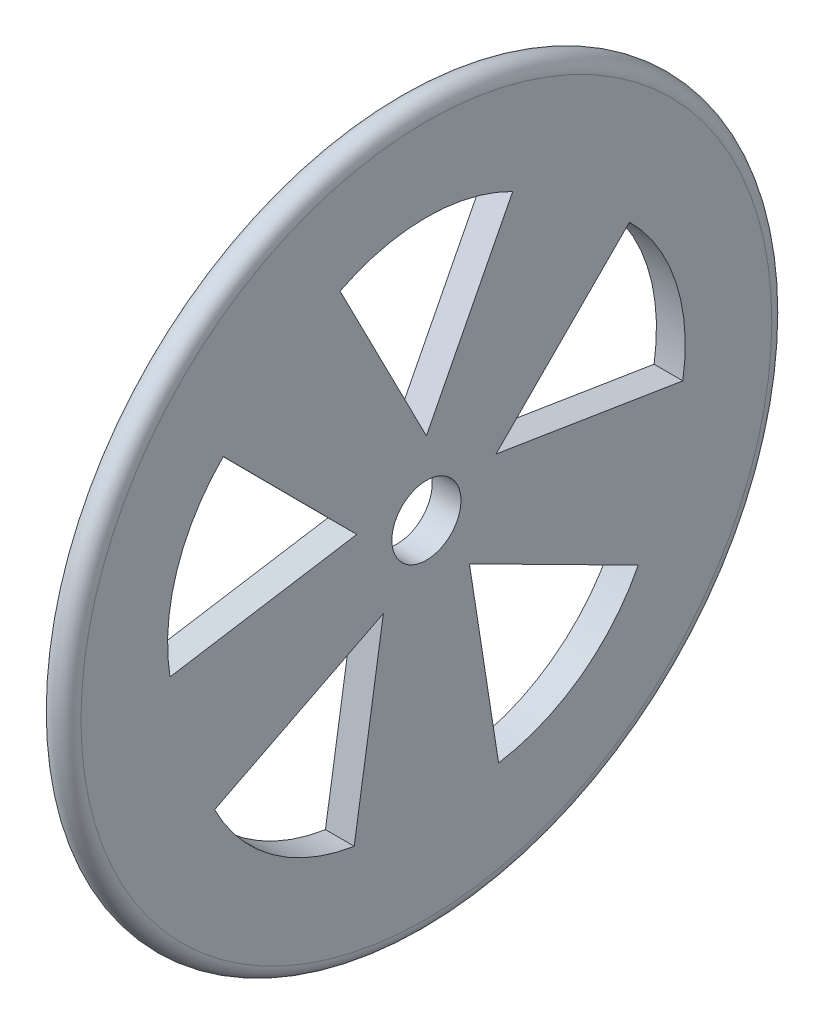
SolidWorks part; units mm, degrees
ref_plane "Front Plane" through (0, 0, 0) normal (0, 0, 1) x (1, 0, 0)
ref_plane "Top Plane" through (0, 0, 0) normal (0, 1, 0) x (1, 0, 0)
ref_plane "Right Plane" through (0, 0, 0) normal (1, 0, 0) x (0, 0, -1)
sketch "Sketch1" plane through (0, 0, 0) normal (0, 0, 1) x (1, 0, 0)
  line L0 (0, 0) -> (0.7937, 0)
  line L1 (0.7937, 0) -> (0.7937, 19.05)
  line L2 (0, 0) -> (-0.7937, 0)
  line L3 (-0.7937, 0) -> (-0.7937, 19.05)
  arc A0 (0.7937, 19.05) -> (-0.7937, 19.05) centre (0, 19.05) ccw
  dimension "D1" = 1.5875
  dimension "D2" = 19.05
revolve "Revolve1" add sketch "Sketch1" angle 360 about L2
sketch "Sketch2" plane through (0.7937, 0, 0) normal (1, 0, 0) x (0, 0, -1)
  line L1 (0, 0) -> (0, 17.4229) construction
  line L3 (0, 4.0369) -> (-4.7603, 13.3241)
  line L4 (0, 4.0369) -> (4.7603, 13.3241)
  line L5 (3.8393, 1.2475) -> (14.143, -0.4099)
  line L6 (3.8393, 1.2475) -> (11.201, 8.6447)
  line L7 (2.3728, -3.2659) -> (3.9806, -13.5774)
  line L8 (2.3728, -3.2659) -> (11.6828, -7.9814)
  line L9 (-2.3728, -3.2659) -> (-11.6828, -7.9814)
  line L10 (-2.3728, -3.2659) -> (-3.9806, -13.5774)
  line L11 (-3.8393, 1.2475) -> (-11.201, 8.6447)
  line L12 (-3.8393, 1.2475) -> (-14.143, -0.4099)
  circle A1 centre (0, 0) radius 1.905
  arc A2 (-4.7603, 13.3241) -> (4.7603, 13.3241) centre (0, 4.0369) cw
  arc A3 (11.201, 8.6447) -> (14.143, -0.4099) centre (3.8393, 1.2475) cw
  arc A4 (11.6828, -7.9814) -> (3.9806, -13.5774) centre (2.3728, -3.2659) cw
  arc A5 (-3.9806, -13.5774) -> (-11.6828, -7.9814) centre (-2.3728, -3.2659) cw
  arc A6 (-14.143, -0.4099) -> (-11.201, 8.6447) centre (-3.8393, 1.2475) cw
  point P5 (0, 0)
  point P8 (0, 0)
  point P22 (0, 0)
  dimension "D1" = 5
extrude "Cut-Extrude1" cut sketch "Sketch2" against normal blind 2.54 contours L3 L1 A2 | L1 L4 A2 | A3 L6 L5 | A4 L8 L7 | A5 L10 L9 | L11 A6 L12 | A1
